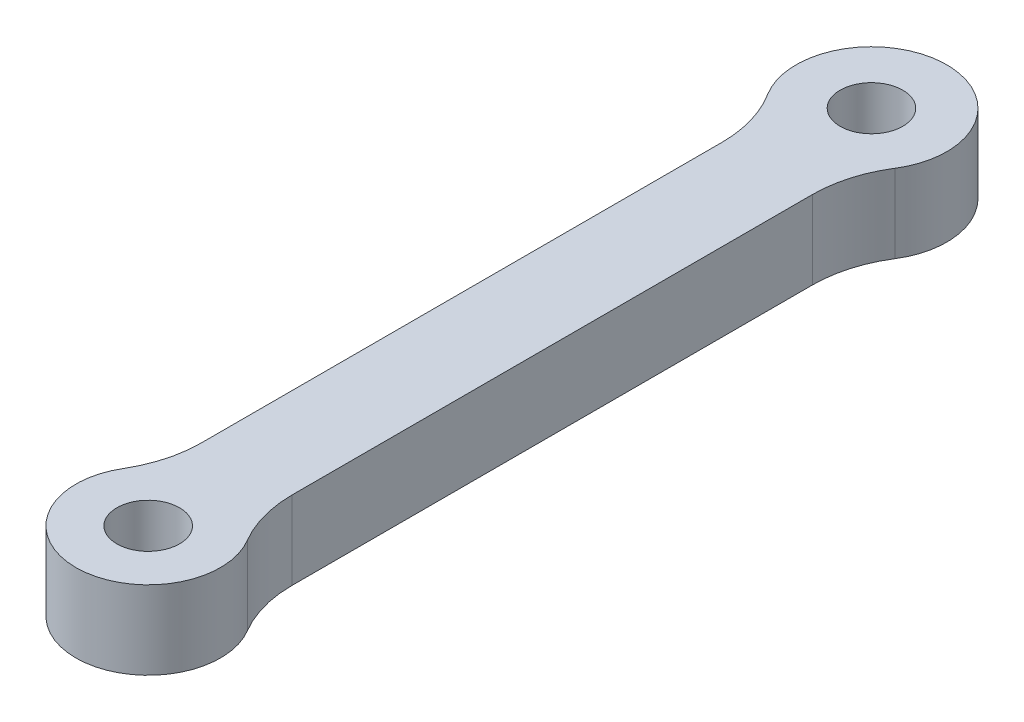
SolidWorks part; units mm, degrees
material "ABS"
ref_plane "Front Plane" through (0, 0, 0) normal (0, 0, 1) x (1, 0, 0)
ref_plane "Top Plane" through (0, 0, 0) normal (0, 1, 0) x (1, 0, 0)
ref_plane "Right Plane" through (0, 0, 0) normal (1, 0, 0) x (0, 0, -1)
sketch "Sketch1" plane through (0, 0, 0) normal (0, 1, 0) x (1, 0, 0)
  line L1 (-3.75, 55) -> (3.75, 55)
  line L2 (-3.75, 55) -> (-3.75, 4.6837)
  line L3 (-3.75, 4.6837) -> (3.75, 4.6837)
  line L4 (3.75, 55) -> (3.75, 4.6837)
  circle A0 centre (0, 0) radius 2.6
  circle A1 centre (0, 60) radius 2.6
  circle A2 centre (0, 60) radius 6.25
  circle A3 centre (0, 0) radius 6
  dimension "D1" = 5.2
  dimension "D2" = 5.2
  dimension "D3" = 12
  dimension "D4" = 12.5
  dimension "D5" = 60
  dimension "D6" = 7.5
extrude "Boss-Extrude1" add sketch "Sketch1" along normal blind 6.5 contours A3 L4 A2 L2 | L3 A3 A0 | L3 A3 | L1 A2 A1
fillet "Fillet1" radius 10 4 edges at (-3.75, 3.25, -4.6837) (-3.75, 3.25, -55) (3.75, 3.25, -4.6837) (3.75, 3.25, -55)
